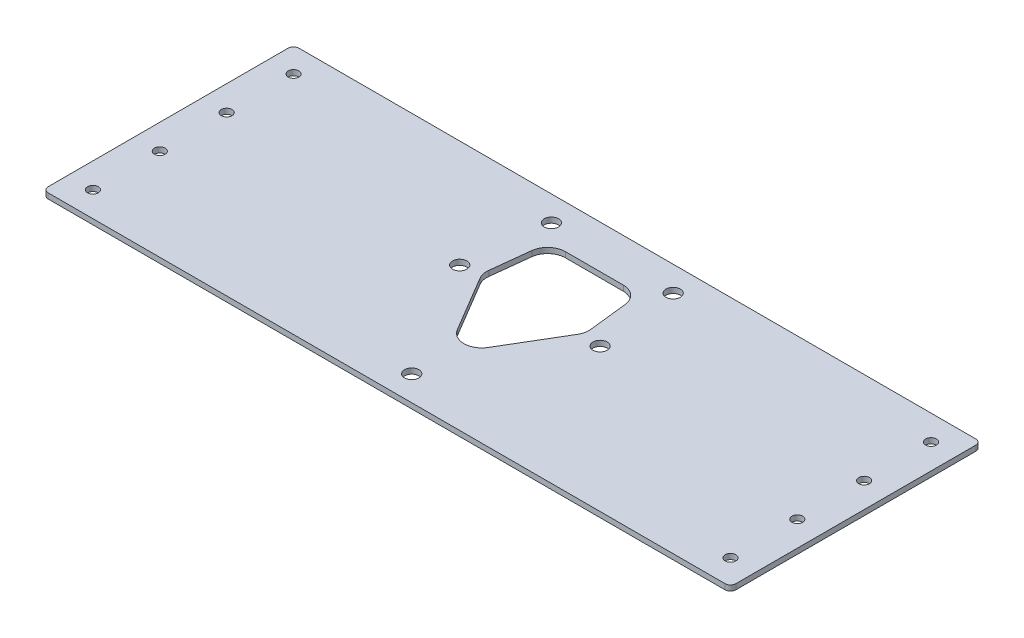
SolidWorks part; units mm, degrees
ref_plane "Front Plane" through (0, 0, 0) normal (0, 0, 1) x (1, 0, 0)
ref_plane "Top Plane" through (0, 0, 0) normal (0, 1, 0) x (1, 0, 0)
ref_plane "Right Plane" through (0, 0, 0) normal (1, 0, 0) x (0, 0, -1)
sketch "Sketch1" plane through (0, 0, 0) normal (0, 1, 0) x (1, 0, 0)
  line L0 (-192, 56) -> (192, 56) construction
  line L1 (-192, 70) -> (192, 70)
  line L2 (-192, 70) -> (-192, -70)
  line L3 (-192, -70) -> (192, -70)
  line L4 (192, 70) -> (192, -70)
  line L5 (-192, 70) -> (192, -70) construction
  line L6 (-192, -70) -> (192, 70) construction
  line L7 (-192, 10) -> (192, 10) construction
  line L8 (-192, -56) -> (192, -56) construction
  line L9 (0, 70) -> (0, -70) construction
  line L10 (-34, 56) -> (34, 56) construction
  line L11 (34, 56) -> (39.2, 10) construction
  line L12 (39.2, 10) -> (0, -56) construction
  line L13 (0, -56) -> (-39.2, 10) construction
  line L14 (-39.2, 10) -> (-34, 56) construction
  line L15 (-28.5082, 15.5566) -> (-26.0702, 37.1233)
  line L16 (-16.1335, 46) -> (16.1335, 46)
  line L17 (26.0702, 37.1233) -> (28.5082, 15.5566)
  line L18 (27.1693, 9.3267) -> (8.5978, -21.9415)
  line L19 (-8.5978, -21.9415) -> (-27.1693, 9.3267)
  line L20 (-28.8857, 12.2167) -> (-25.0667, 46) construction
  line L21 (0, -36.4175) -> (-28.8857, 12.2167) construction
  line L22 (28.8857, 12.2167) -> (0, -36.4175) construction
  line L23 (25.0667, 46) -> (28.8857, 12.2167) construction
  line L24 (-25.0667, 46) -> (25.0667, 46) construction
  line L25 (-178, -70) -> (-178, 70) construction
  line L26 (-192, 0) -> (192, 0) construction
  line L27 (-175, 56) -> (-175, 18.6667) construction
  line L28 (-181, 18.6667) -> (-181, -18.6667) construction
  circle A0 centre (-34, 56) radius 4
  circle A1 centre (-39.2, 10) radius 4
  circle A2 centre (0, -56) radius 4
  circle A3 centre (39.2, 10) radius 4
  circle A4 centre (34, 56) radius 4
  arc A5 (-28.5082, 15.5566) -> (-27.1693, 9.3267) centre (-18.5715, 14.4333) ccw
  arc A6 (8.5978, -21.9415) -> (-8.5978, -21.9415) centre (0, -16.8349) cw
  arc A7 (28.5082, 15.5566) -> (27.1693, 9.3267) centre (18.5715, 14.4333) cw
  arc A8 (16.1335, 46) -> (26.0702, 37.1233) centre (16.1335, 36) cw
  arc A9 (-26.0702, 37.1233) -> (-16.1335, 46) centre (-16.1335, 36) cw
  circle A10 centre (-178, -56) radius 3
  circle A11 centre (178, -56) radius 3
  circle A12 centre (-178, 56) radius 3
  circle A13 centre (178, 56) radius 3
  circle A16 centre (-178, 18.6667) radius 3
  circle A17 centre (-178, -18.6667) radius 3
  circle A18 centre (178, 18.6667) radius 3
  circle A19 centre (178, -18.6667) radius 3
  point P0 (0, 0)
  dimension "D6" = 8
  dimension "D10" = 10
  dimension "D12" = 6
  dimension "D1" = 126
  dimension "D2" = 384
  dimension "D3" = 14
  dimension "D4" = 80
  dimension "D5" = 140
  dimension "D7" = 68
  dimension "D8" = 78.4
  dimension "D11" = 14
  dimension "D9" = 10
extrude "Boss-Extrude1" add sketch "Sketch1" along normal blind 3
fillet "Fillet1" radius 3 4 edges at (-192, 1.5, -70) (192, 1.5, -70) (192, 1.5, 70) (-192, 1.5, 70)
